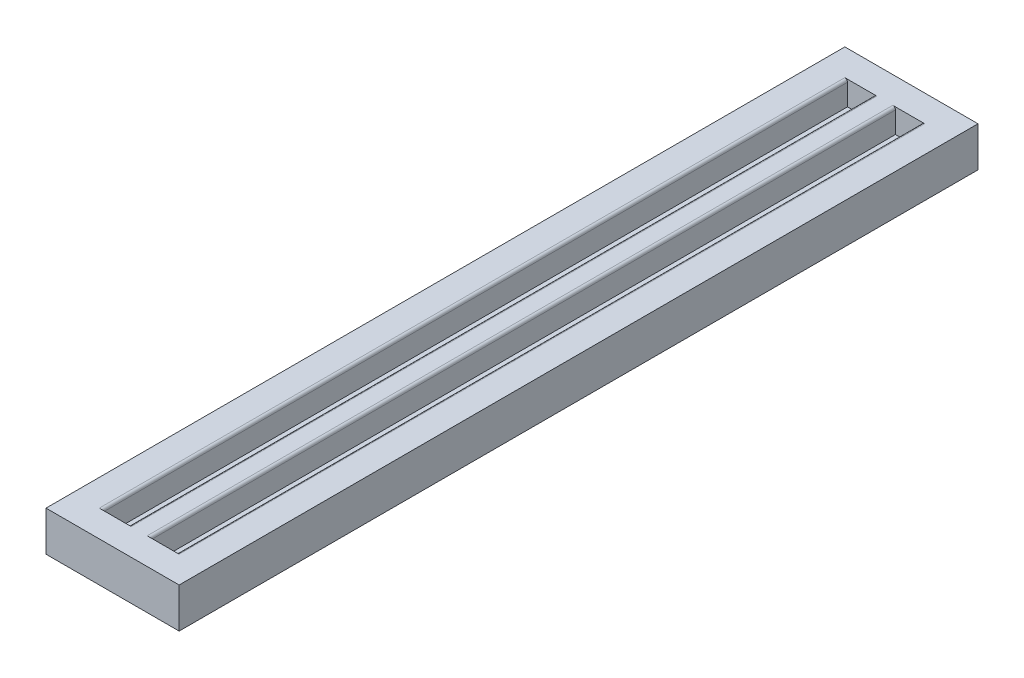
SolidWorks part; units mm, degrees
ref_plane "Front Plane" through (0, 0, 0) normal (0, 0, 1) x (1, 0, 0)
ref_plane "Top Plane" through (0, 0, 0) normal (0, 1, 0) x (1, 0, 0)
ref_plane "Right Plane" through (0, 0, 0) normal (1, 0, 0) x (0, 0, -1)
other "Configuration Table"
sketch "Sketch1" plane through (0, 0, 0) normal (0, 0, 1) x (1, 0, 0)
  line L1 (125, 37.5) -> (-125, 37.5)
  line L2 (125, 37.5) -> (125, -37.5)
  line L3 (125, -37.5) -> (-125, -37.5)
  line L4 (-125, 37.5) -> (-125, -37.5)
  line L5 (125, 37.5) -> (-125, -37.5) construction
  line L6 (125, -37.5) -> (-125, 37.5) construction
  point P0 (0, 0)
  dimension "D1" = 250
  dimension "D2" = 75
extrude "Boss-Extrude1" add sketch "Sketch1" along normal mid plane 1500
sketch "Sketch2" plane through (0, 0, 0) normal (0, 0, 1) x (1, 0, 0)
  line L0 (125, 37.5) -> (-125, 37.5) construction
  line L1 (-70, 37.5) -> (-20, 37.5)
  line L2 (-70, 37.5) -> (-70, -7.5)
  line L3 (-70, -7.5) -> (-20, -7.5)
  line L4 (-20, 37.5) -> (-20, -7.5)
  line L5 (0, 46.1769) -> (0, -50.5021) construction
  line L6 (20, 37.5) -> (70, 37.5)
  line L7 (20, 37.5) -> (20, -7.5)
  line L8 (20, -7.5) -> (70, -7.5)
  line L9 (70, 37.5) -> (70, -7.5)
  dimension "D1" = 50
  dimension "D2" = 45
  dimension "D3" = 20
extrude "Cut-Extrude1" cut sketch "Sketch2" against normal mid plane 1400
fillet "Fillet1" radius 5 4 edges at (70, 37.5, 0) (20, 37.5, 0) (-20, 37.5, 0) (-70, 37.5, 0)
